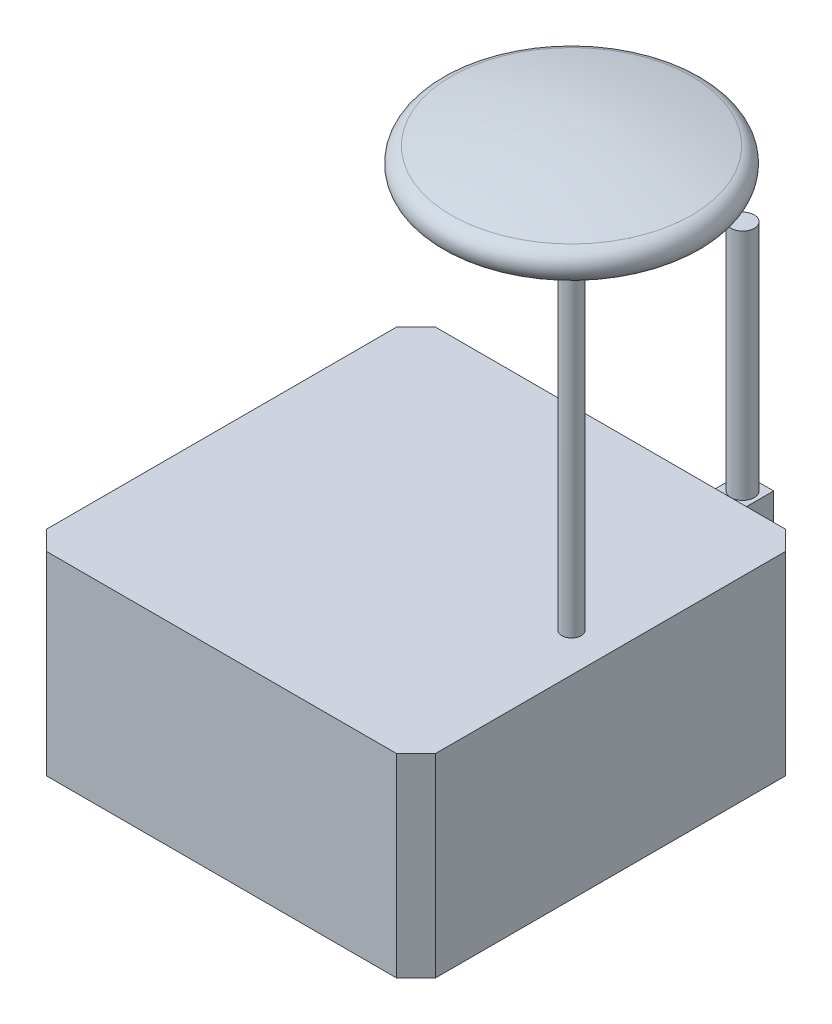
SolidWorks part; units mm, degrees
ref_plane "前基準面" through (0, 0, 0) normal (0, 0, 1) x (1, 0, 0)
ref_plane "上基準面" through (0, 0, 0) normal (0, 1, 0) x (1, 0, 0)
ref_plane "右基準面" through (0, 0, 0) normal (1, 0, 0) x (0, 0, -1)
sketch "草圖1" plane through (0, 0, 0) normal (0, 1, 0) x (1, 0, 0)
  line L0 (-50, 45) -> (-50, -45)
  line L1 (-45, 50) -> (45, 50)
  line L2 (-45, -50) -> (45, -50)
  line L3 (50, 45) -> (50, -45)
  line L4 (-50, 50) -> (50, -50) construction
  line L5 (-50, -50) -> (50, 50) construction
  line L6 (-50, 45) -> (-45, 50)
  line L7 (45, 50) -> (50, 45)
  line L8 (45, -50) -> (50, -45)
  line L9 (-50, -45) -> (-45, -50)
  point P1 (0, 0)
  dimension "D1" = 100
  dimension "D2" = 100
extrude "填料-伸長1" add sketch "草圖1" along normal blind 50
sketch "草圖2" plane through (0, 50, 0) normal (0, 1, 0) x (1, 0, 0)
  line L0 (0, 0) -> (50, 0) construction
  line L1 (50, -45) -> (50, 45) construction
  circle A0 centre (40, 0) radius 2.5
  point P7 (0, 0)
  dimension "D1" = 5
  dimension "D2" = 10
extrude "填料-伸長2" add sketch "草圖2" along normal blind 100
sketch "草圖4" plane through (0, 0, 0) normal (0, 0, 1) x (1, 0, 0)
  line L0 (40, 150) -> (40, 161.8807)
  line L1 (42.5, 150) -> (37.5, 150) construction
  line L2 (40, 150) -> (70, 150)
  arc A0 (70, 150) -> (70.946, 157.8865) centre (70, 154) ccw
  spline S0 degree 3 poles (40, 161.8807) (49.3625, 162.2247) (61.6441, 160.1507) (70.946, 157.8865) knots 0 0 0 0 1 1 1 1
  point P8 (70, 160.0926)
  point P9 (70.946, 157.8865)
  dimension "D2" = 4
  dimension "D1" = 30
revolve "旋轉1" add sketch "草圖4" angle 360 about L0
sketch "草圖5" plane through (0, 0, -50) normal (0, 0, -1) x (-1, 0, 0)
  line L0 (-25, 40) -> (-25, 50) construction
  line L1 (-45, 50) -> (45, 50) construction
  line L2 (-45, 50) -> (-45, 0) construction
  circle A0 centre (-25, 40) radius 2.5
  dimension "D1" = 5
  dimension "D2" = 10
  dimension "D3" = 20
extrude "填料-伸長3" add sketch "草圖5" along normal blind 5
sketch "草圖6" plane through (0, 0, -55) normal (0, 0, -1) x (-1, 0, 0)
  line L1 (-29, 44) -> (-21, 44)
  line L2 (-29, 44) -> (-29, 36)
  line L3 (-29, 36) -> (-21, 36)
  line L4 (-21, 44) -> (-21, 36)
  line L5 (-29, 44) -> (-21, 36) construction
  line L6 (-29, 36) -> (-21, 44) construction
  point P0 (-25, 40)
  dimension "D1" = 8
extrude "填料-伸長4" add sketch "草圖6" along normal blind 8
sketch "草圖7" plane through (0, 44, 0) normal (0, 1, 0) x (1, 0, 0)
  line L1 (21, 55) -> (29, 63) construction
  circle A0 centre (25, 59) radius 3
  dimension "D1" = 6
extrude "填料-伸長5" add sketch "草圖7" along normal blind 60
